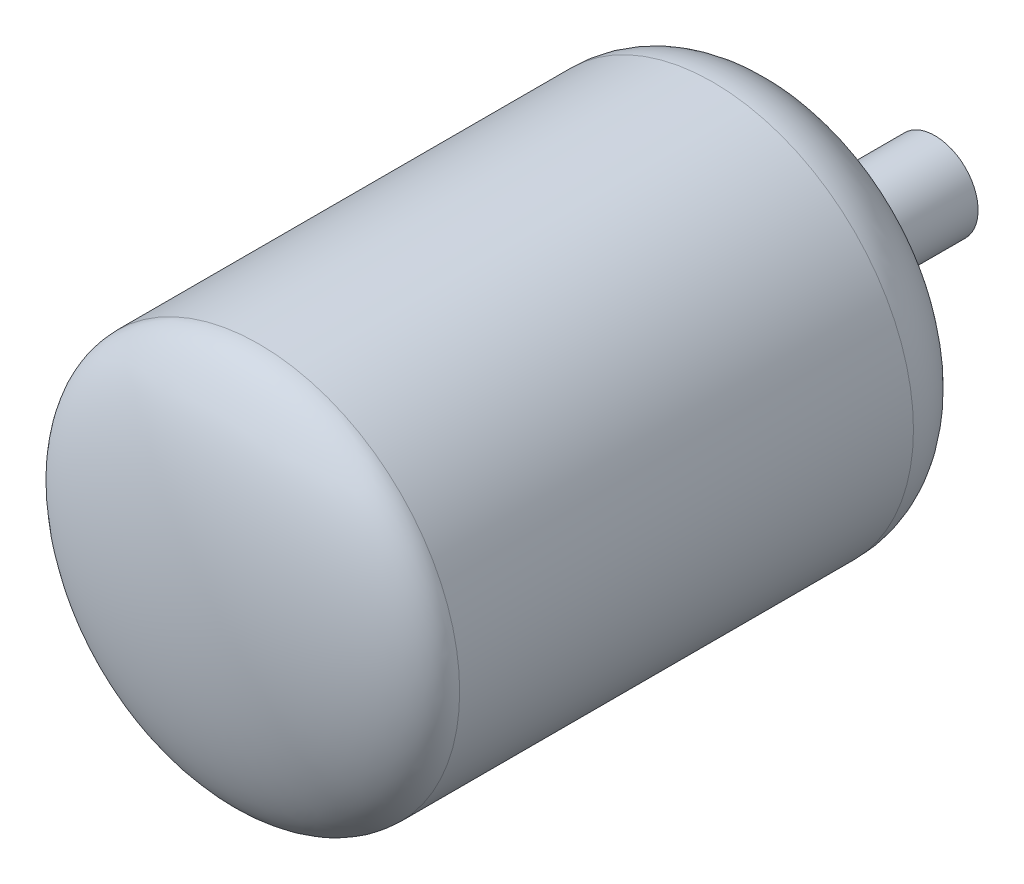
SolidWorks part; units mm, degrees
other "DetailItem1"
ref_plane "Front Plane" through (0, 0, 0) normal (1, 0, 0) x (0, 1, 0)
ref_plane "Top Plane" through (0, 0, 0) normal (0, 0, 1) x (0, 1, 0)
ref_plane "Right Plane" through (0, 0, 0) normal (0, 1, 0) x (-1, 0, 0)
sketch "Sketch1" plane through (0, 0, 0) normal (1, 0, 0) x (0, 1, 0)
  line L0 (0, 0) -> (12, 0)
  line L1 (12, 0) -> (12, 25)
  line L2 (12, 25) -> (45.88, 44.5606)
  line L3 (55.88, 61.8811) -> (55.88, 188.28)
  line L4 (0, 0) -> (0, 208.28)
  arc A0 (45.88, 44.5606) -> (55.88, 61.8811) centre (35.88, 61.8811) ccw
  ellipse E0 centre (0, 188.28) end of major axis (55.88, 188.28) minor radius 20 (0, 208.28) -> (55.88, 188.28) cw
  dimension "D4" = 20
  dimension "D1" = 55.88
  dimension "D2" = 208.28
  dimension "D3" = 12
  dimension "D5" = 60
  dimension "D6" = 25
  dimension "D7" = 20
revolve "Revolve1" add sketch "Sketch1" angle 360 about L4
